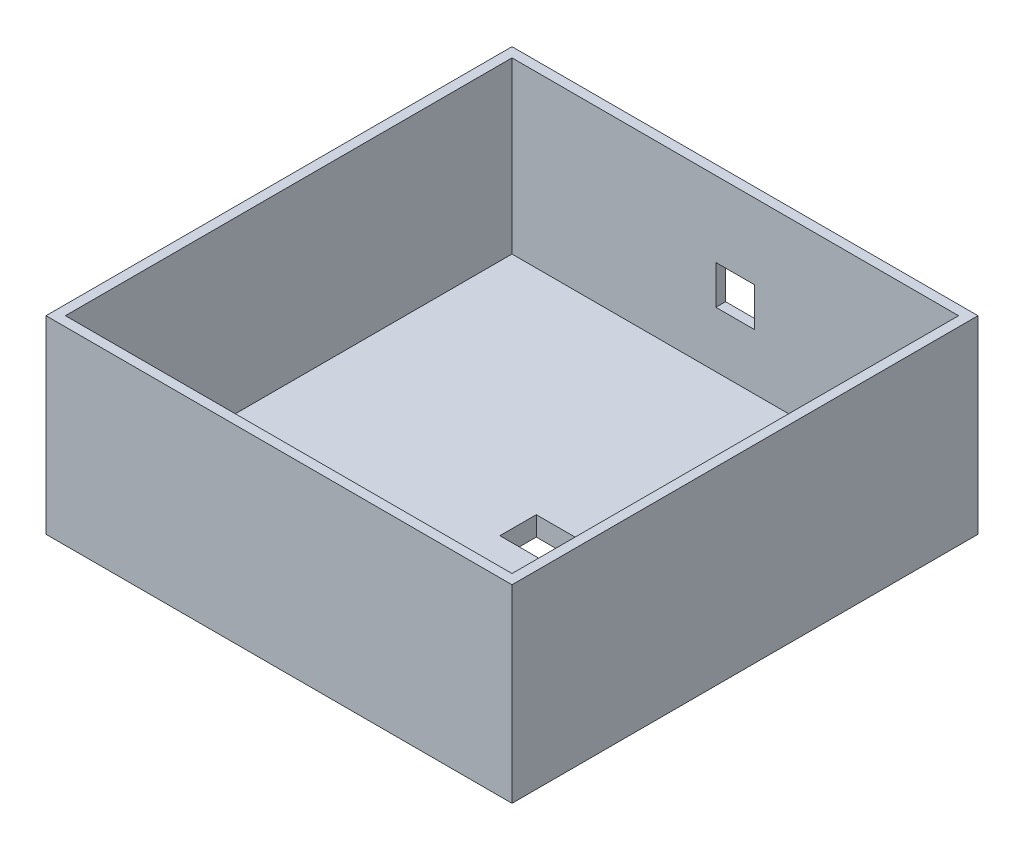
SolidWorks part; units mm, degrees
ref_plane "Front Plane" through (0, 0, 0) normal (0, 0, 1) x (1, 0, 0)
ref_plane "Top Plane" through (0, 0, 0) normal (0, 1, 0) x (1, 0, 0)
ref_plane "Right Plane" through (0, 0, 0) normal (1, 0, 0) x (0, 0, -1)
sketch "Sketch1" plane through (0, 0, 0) normal (0, 1, 0) x (1, 0, 0)
  line L1 (-50, -50) -> (50, -50)
  line L2 (-50, -50) -> (-50, 50)
  line L3 (-50, 50) -> (50, 50)
  line L4 (50, -50) -> (50, 50)
  line L5 (-50, -50) -> (50, 50) construction
  line L6 (-50, 50) -> (50, -50) construction
  point P0 (0, 0)
  dimension "D1" = 100
extrude "Boss-Extrude1" add sketch "Sketch1" along normal blind 4
sketch "Sketch2" plane through (0, 4, 0) normal (0, 1, 0) x (1, 0, 0)
  line L0 (46, -46) -> (46, 46)
  line L1 (46, 46) -> (-46, 46)
  line L2 (-46, 46) -> (-46, -46)
  line L3 (-46, -46) -> (46, -46)
  line L4 (50, -50) -> (50, 50)
  line L5 (50, 50) -> (-50, 50)
  line L6 (-50, 50) -> (-50, -50)
  line L7 (-50, -50) -> (50, -50)
  line L8 (50, -50) -> (50, 50)
  line L9 (50, 50) -> (-50, 50)
  line L10 (-50, 50) -> (-50, -50)
  line L11 (-50, -50) -> (50, -50)
  dimension "D1" = 0
  dimension "D2" = 4
extrude "Boss-Extrude2" add sketch "Sketch2" along normal blind 35
sketch "Sketch3" plane through (0, 0, -50) normal (0, 0, -1) x (-1, 0, 0)
  line L0 (-50, 39) -> (50, 39) construction
  line L1 (2, 35) -> (-2, 35)
  line L2 (2, 35) -> (2, 39)
  line L3 (2, 39) -> (-2, 39)
  line L4 (-2, 35) -> (-2, 39)
  line L5 (2, 35) -> (-2, 39) construction
  line L6 (2, 39) -> (-2, 35) construction
  point P0 (0, 37)
  dimension "D1" = 4
extrude "Cut-Extrude1" cut sketch "Sketch3" against normal up to surface (4 mm away) up to face at (0, 21.5, -46)
sketch "Sketch4" plane through (0, 4, 0) normal (0, 1, 0) x (1, 0, 0)
  line L1 (9.75, -0.5) -> (-1.75, -0.5)
  line L2 (9.75, -0.5) -> (9.75, -17)
  line L3 (9.75, -17) -> (-1.75, -17)
  line L4 (-1.75, -0.5) -> (-1.75, -17)
  line L5 (9.75, -0.5) -> (-1.75, -17) construction
  line L6 (9.75, -17) -> (-1.75, -0.5) construction
  line L7 (14, 19) -> (-6, 19)
  line L8 (14, 19) -> (14, -21)
  line L9 (14, -21) -> (-6, -21)
  line L10 (-6, 19) -> (-6, -21)
  line L11 (14, 19) -> (-6, -21) construction
  line L12 (14, -21) -> (-6, 19) construction
  line L17 (-46, -46) -> (46, -46) construction
  line L26 (46, -46) -> (46, 46) construction
  line L28 (12.25, -19.5) -> (7.25, -19.5)
  line L29 (12.25, -19.5) -> (12.25, -14.5)
  line L30 (12.25, -14.5) -> (7.25, -14.5)
  line L31 (7.25, -19.5) -> (7.25, -14.5)
  line L32 (12.25, -19.5) -> (7.25, -14.5) construction
  line L33 (12.25, -14.5) -> (7.25, -19.5) construction
  line L34 (-4.25, -19.5) -> (0.75, -19.5)
  line L35 (-4.25, -19.5) -> (-4.25, -14.5)
  line L36 (-4.25, -14.5) -> (0.75, -14.5)
  line L37 (0.75, -19.5) -> (0.75, -14.5)
  line L38 (-4.25, -19.5) -> (0.75, -14.5) construction
  line L39 (-4.25, -14.5) -> (0.75, -19.5) construction
  line L40 (12.25, 2) -> (7.25, 2)
  line L41 (12.25, 2) -> (12.25, -3)
  line L42 (12.25, -3) -> (7.25, -3)
  line L43 (7.25, 2) -> (7.25, -3)
  line L44 (12.25, 2) -> (7.25, -3) construction
  line L45 (12.25, -3) -> (7.25, 2) construction
  line L46 (-4.25, 2) -> (0.75, 2)
  line L47 (-4.25, 2) -> (-4.25, -3)
  line L48 (-4.25, -3) -> (0.75, -3)
  line L49 (0.75, 2) -> (0.75, -3)
  line L50 (-4.25, 2) -> (0.75, -3) construction
  line L51 (-4.25, -3) -> (0.75, 2) construction
  point P0 (4, -8.75)
  point P5 (4, -1)
  dimension "D1" = 11.5
  dimension "D2" = 16.5
  dimension "D3" = 32
  dimension "D4" = 25
  dimension "D5" = 40
  dimension "D6" = 20
  dimension "D7" = 4
  dimension "D8" = 2.5
  dimension "D9" = 2.5
extrude "Boss-Extrude3" add sketch "Sketch4" along normal blind 2.5 contours L49 L46 L47 L48 L4 L1 | L40 L43 L1 L2 L42 L41 | L31 L28 L29 L30 L2 L3 | L34 L37 L3 L4 L36 L35
sketch "Sketch5" plane through (0, 4, 0) normal (0, 1, 0) x (1, 0, 0)
  line L1 (4, -13) -> (-1.75, -13)
  line L2 (4, -13) -> (4, -17)
  line L3 (4, -17) -> (-1.75, -17)
  line L4 (-1.75, -13) -> (-1.75, -17)
  line L5 (4, -13) -> (-1.75, -17) construction
  line L6 (4, -17) -> (-1.75, -13) construction
  point P0 (1.125, -15)
  dimension "D1" = 4
  dimension "D2" = 5.75
extrude "Cut-Extrude2" cut sketch "Sketch5" against normal up to surface (4 mm away) up to face at (0, 0, 0)
sketch "Sketch7" plane through (0, 4, 0) normal (0, 1, 0) x (1, 0, 0)
  line L0 (4, -13) -> (-1.75, -13) construction
  line L1 (-4.25, -19.5) -> (5, -19.5)
  line L2 (-4.25, -19.5) -> (-4.25, -12)
  line L3 (-4.25, -12) -> (5, -12)
  line L4 (5, -19.5) -> (5, -12)
  line L5 (4, -17) -> (4, -13) construction
  line L7 (12.25, 2) -> (3, 2)
  line L8 (12.25, 2) -> (12.25, -5.5)
  line L9 (12.25, -5.5) -> (3, -5.5)
  line L10 (3, 2) -> (3, -5.5)
  point P9 (4, -15)
  dimension "D1" = 1
  dimension "D2" = 1
  dimension "D3" = 9.25
  dimension "D4" = 7.5
extrude "Cut-Extrude3" cut sketch "Sketch7" against normal through all both and the other way through all
sketch "Sketch8" plane through (0, 4, 0) normal (0, 1, 0) x (1, 0, 0)
  line L1 (-4.7402, 2.9437) -> (1.459, 2.9437)
  line L2 (-4.7402, 2.9437) -> (-4.7402, -3.76)
  line L3 (-4.7402, -3.76) -> (1.459, -3.76)
  line L4 (1.459, 2.9437) -> (1.459, -3.76)
  line L5 (6.2886, -13.3471) -> (13.8574, -13.3471)
  line L6 (6.2886, -13.3471) -> (6.2886, -20.5555)
  line L7 (6.2886, -20.5555) -> (13.8574, -20.5555)
  line L8 (13.8574, -13.3471) -> (13.8574, -20.5555)
extrude "Cut-Extrude5" cut sketch "Sketch8" along normal blind 10
sketch "Sketch9" plane through (0, 0, -50) normal (0, 0, -1) x (-1, 0, 0)
  line L0 (-2, 39) -> (-2, 35) construction
  line L1 (-6, 23.5) -> (6, 23.5)
  line L2 (-6, 23.5) -> (-6, 15.5)
  line L3 (-6, 15.5) -> (6, 15.5)
  line L4 (6, 23.5) -> (6, 15.5)
  line L5 (2, 35) -> (2, 39) construction
  line L9 (-50, 39) -> (-2, 39) construction
  dimension "D1" = 4
  dimension "D2" = 4
  dimension "D3" = 8
  dimension "D4" = 15.5
extrude "Cut-Extrude6" cut sketch "Sketch9" against normal blind 10
sketch "Sketch10" plane through (0, 0, -50) normal (0, 0, -1) x (-1, 0, 0)
  line L1 (-2, 35) -> (2, 35)
  line L2 (-2, 35) -> (-2, 39)
  line L3 (-2, 39) -> (2, 39)
  line L4 (2, 35) -> (2, 39)
extrude "Boss-Extrude4" add sketch "Sketch10" against normal blind 4
sketch "Sketch11" plane through (0, 39, 0) normal (0, 1, 0) x (1, 0, 0)
  line L0 (-50, 50) -> (-50, -50) construction
  line L1 (-48, 48) -> (48, 48)
  line L2 (-48, 48) -> (-48, -48)
  line L3 (-48, -48) -> (48, -48)
  line L4 (48, 48) -> (48, -48)
  line L5 (50, 50) -> (-50, 50) construction
  line L6 (-46, -46) -> (46, -46) construction
  line L7 (46, -46) -> (46, 46) construction
  dimension "D1" = 2
  dimension "D2" = 2
  dimension "D3" = 2
  dimension "D4" = 2
extrude "Cut-Extrude7" cut sketch "Sketch11" against normal through all flip side to cut
sketch "Sketch12" plane through (0, 0, -48) normal (0, 0, -1) x (-1, 0, 0)
  line L0 (6, 15.5) -> (-6, 15.5) construction
  line L1 (-6, 23.5) -> (-4, 23.5)
  line L2 (-6, 23.5) -> (-6, 15.5)
  line L3 (-6, 15.5) -> (-4, 15.5)
  line L4 (-4, 23.5) -> (-4, 15.5)
  line L6 (6, 23.5) -> (4, 23.5)
  line L7 (6, 23.5) -> (6, 15.5)
  line L8 (6, 15.5) -> (4, 15.5)
  line L9 (4, 23.5) -> (4, 15.5)
  dimension "D1" = 2
  dimension "D2" = 2
extrude "Boss-Extrude5" add sketch "Sketch12" against normal blind 2
